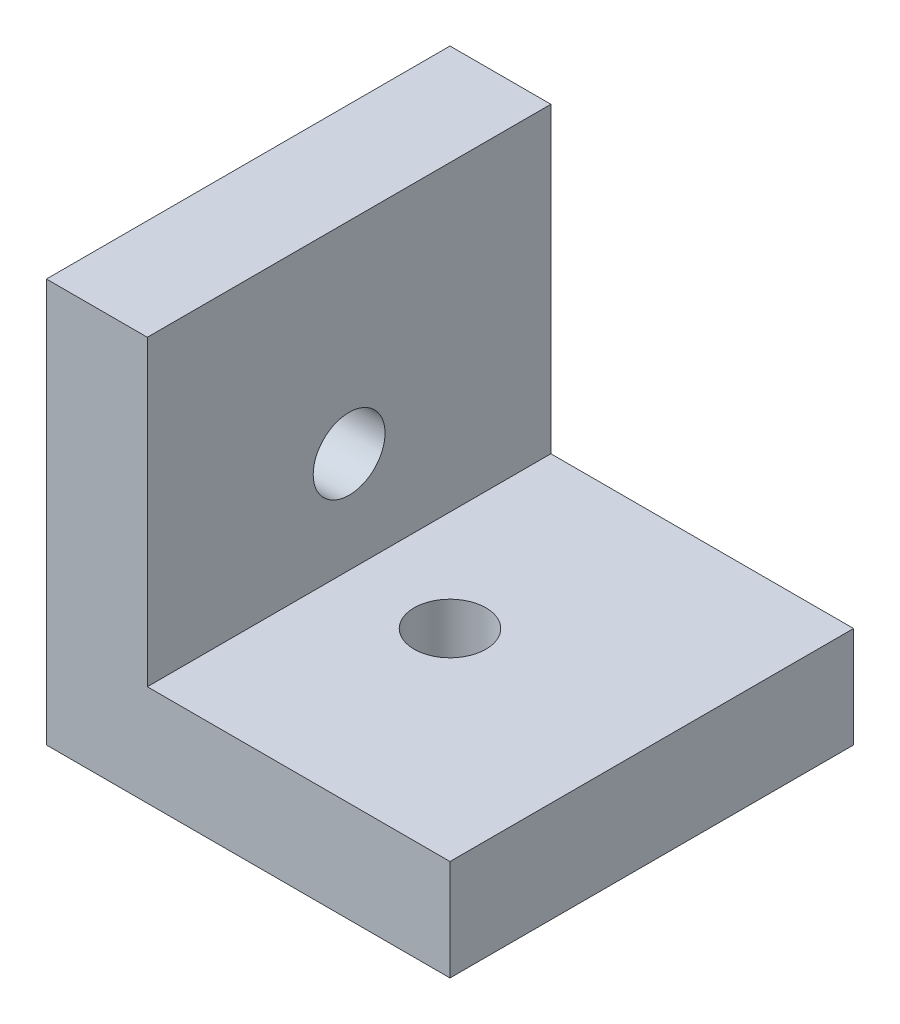
SolidWorks part; units mm, degrees
material "6061 Alloy"
ref_plane "Front Plane" through (0, 0, 0) normal (0, 0, 1) x (1, 0, 0)
ref_plane "Top Plane" through (0, 0, 0) normal (0, 1, 0) x (1, 0, 0)
ref_plane "Right Plane" through (0, 0, 0) normal (1, 0, 0) x (0, 0, -1)
sketch "Sketch1" plane through (0, 0, 0) normal (0, 0, 1) x (1, 0, 0)
  line L1 (-0.5202, 11.7281) -> (2.6548, 11.7281)
  line L2 (-0.5202, 11.7281) -> (-0.5202, -0.9719)
  line L3 (-0.5202, -0.9719) -> (12.1798, -0.9719)
  line L4 (12.1798, 2.2031) -> (12.1798, -0.9719)
  line L7 (12.1798, 2.2031) -> (2.6548, 2.2031)
  line L8 (2.6548, 11.7281) -> (2.6548, 2.2031)
  dimension "D1" = 12.7
  dimension "D2" = 12.7
  dimension "D3" = 3.175
  dimension "D4" = 3.175
extrude "Boss-Extrude1" add sketch "Sketch1" along normal blind 12.7
hole_wizard "#4-40 Tapped Hole1" positions "3DSketch1" profile "Sketch2" tap size "#4-40" standard "ANSI Inch"
sketch3d "3DSketch1"
  line L0 (-0.5202, 11.7281, 12.7) -> (-0.5202, 11.7281, 0) construction
  line L1 (-0.5202, 11.7281, 12.7) -> (-0.5202, -0.9719, 12.7) construction
  line L2 (12.1798, -0.9719, 12.7) -> (12.1798, -0.9719, 0) construction
  line L3 (-0.5202, -0.9719, 12.7) -> (12.1798, -0.9719, 12.7) construction
  point P0 (-0.5202, 5.3781, 6.35)
  point P2 (5.8298, -0.9719, 6.35)
  dimension "D1" = 6.35
  dimension "D2" = 6.35
  dimension "D3" = 6.35
  dimension "D4" = 6.35
sketch "Sketch2" plane through (-0.5202, 5.3781, 6.35) normal (0, 1, 0) x (0, 0, 1)
  line L0 (0, 0) -> (0, 8.2992)
  line L1 (0, 8.2992) -> (1.1303, 7.62)
  line L2 (1.1303, 7.62) -> (1.1303, 0)
  line L5 (1.1303, 0) -> (0, 0)
  line L10 (0, 8.2992) -> (-1.1303, 7.62) construction
  line L11 (0, -6.35) -> (0, 107.95) construction
  dimension "Tap Drill Dia." = 2.2606
  dimension "Tap Drill Depth" = 7.62
  dimension "Drill Angle" = 118
